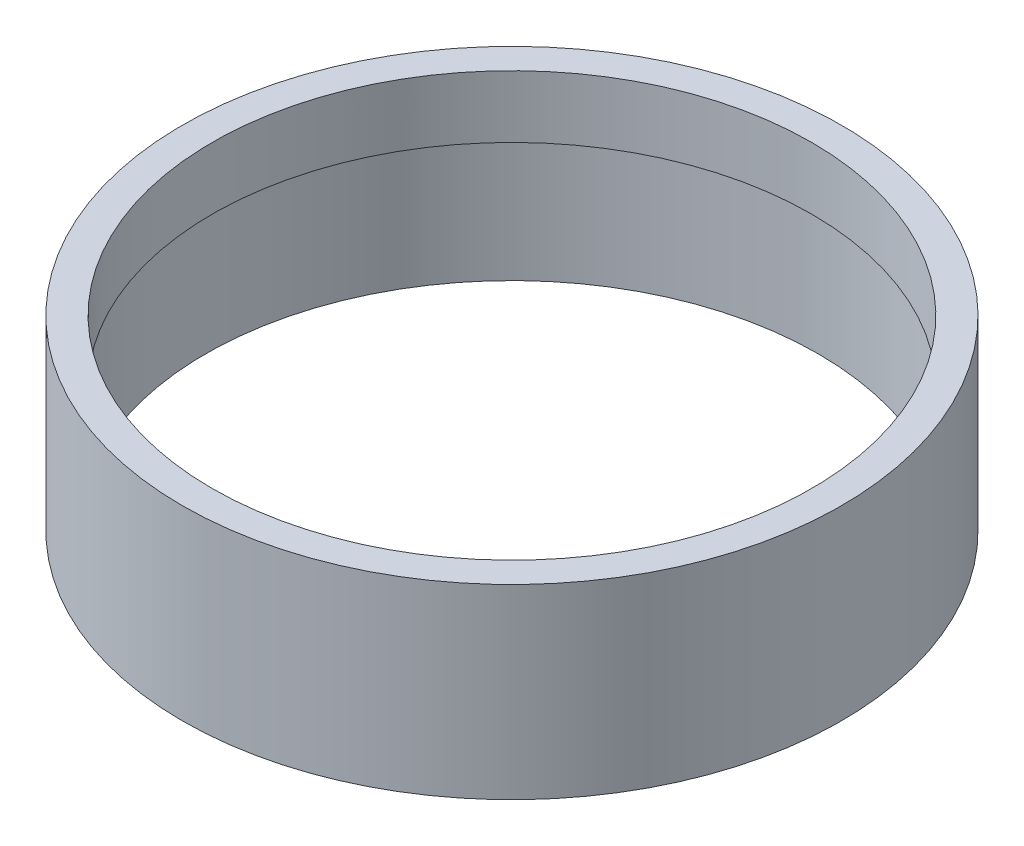
SolidWorks part; units mm, degrees
ref_plane "Front" through (0, 0, 0) normal (0, 0, 1) x (1, 0, 0)
ref_plane "Top" through (0, 0, 0) normal (0, 1, 0) x (1, 0, 0)
ref_plane "Right" through (0, 0, 0) normal (1, 0, 0) x (0, 0, -1)
sketch "Sketch1" plane through (0, 0, 0) normal (0, 1, 0) x (1, 0, 0)
  circle A0 centre (0, 0) radius 24.125
  circle A1 centre (0, 0) radius 26.525
  dimension "D1" = 48.25
  dimension "D2" = 2.4
extrude "Boss-Extrude1" add sketch "Sketch1" along normal blind 15
sketch "Sketch2" plane through (0, 0, 0) normal (0, -1, 0) x (1, 0, 0)
  circle A0 centre (0, 0) radius 24.65
  dimension "D1" = 49.3
extrude "Cut-Extrude1" cut sketch "Sketch2" against normal blind 10
